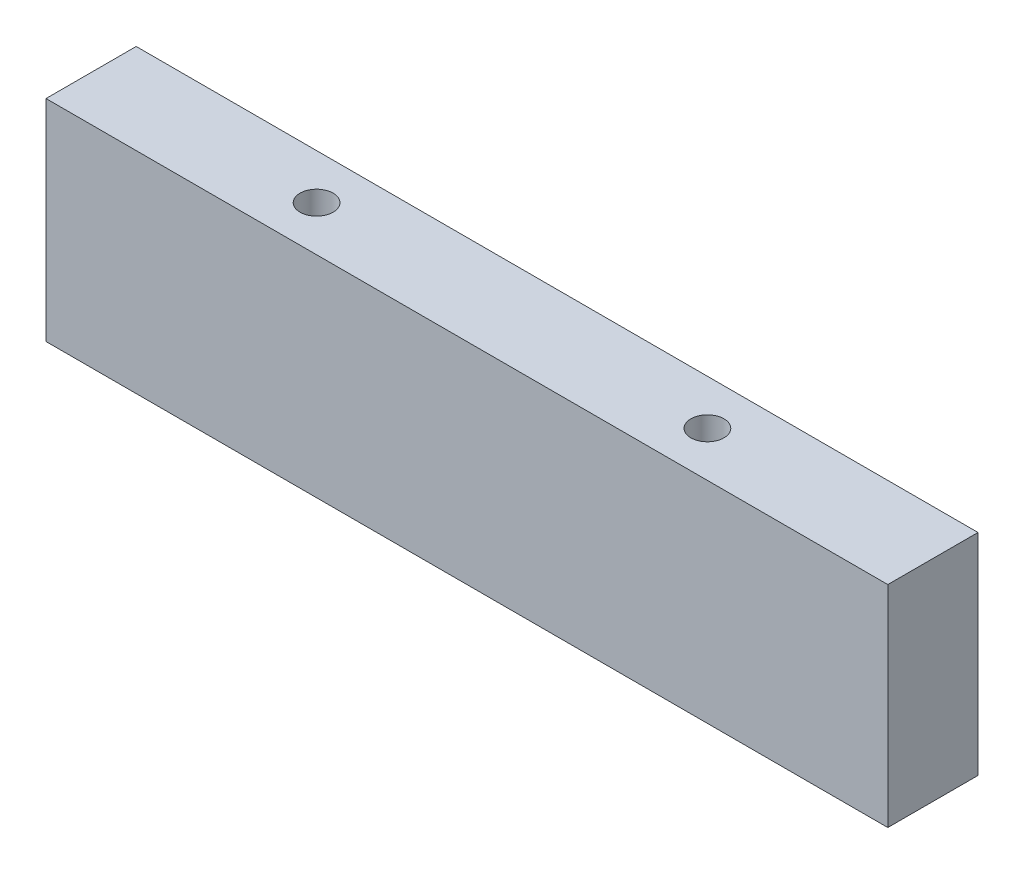
SolidWorks part; units mm, degrees
ref_plane "Front Plane" through (0, 0, 0) normal (0, 0, 1) x (1, 0, 0)
ref_plane "Top Plane" through (0, 0, 0) normal (0, 1, 0) x (1, 0, 0)
ref_plane "Right Plane" through (0, 0, 0) normal (1, 0, 0) x (0, 0, -1)
sketch "Sketch1" plane through (0, 0, 0) normal (0, 0, 1) x (1, 0, 0)
  line L1 (-140, -35) -> (140, -35)
  line L2 (-140, -35) -> (-140, 35)
  line L3 (-140, 35) -> (140, 35)
  line L4 (140, -35) -> (140, 35)
  point P0 (0, 0)
extrude "Boss-Extrude1" add sketch "Sketch1" along normal blind 30
sketch "Sketch2" plane through (0, 35, 0) normal (0, 1, 0) x (1, 0, 0)
  line L0 (-140, -30) -> (-140, 0) construction
  circle A0 centre (-65, -15) radius 5.5
  circle A1 centre (65, -15) radius 5.5
  point P0 (0, 0)
  dimension "D1" = 2
  dimension "D2" = 75
  dimension "D3" = 130
extrude "Cut-Extrude1" cut sketch "Sketch2" against normal blind 80 contours A0 | A1
